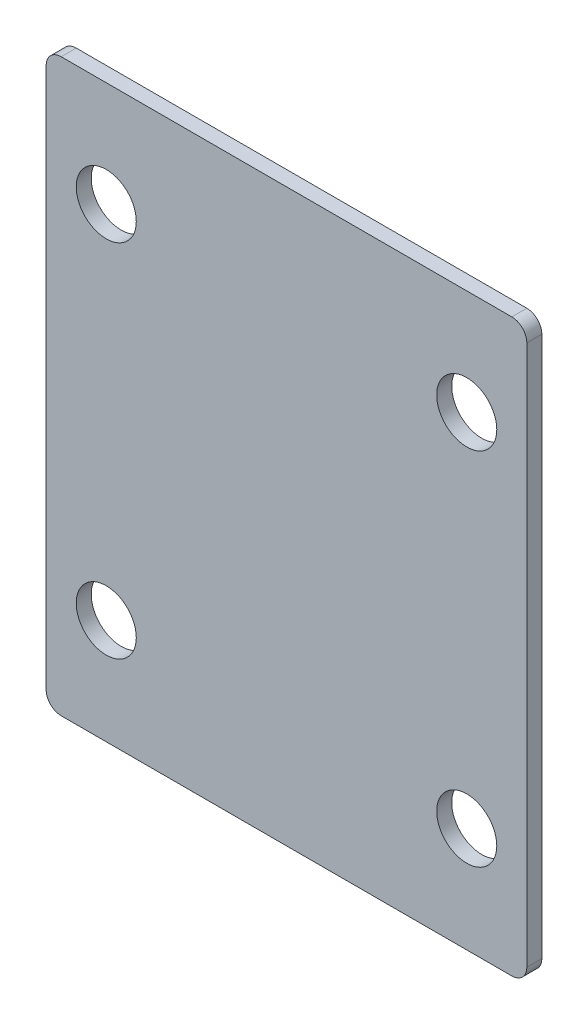
SolidWorks part; units mm, degrees
ref_plane "Front Plane" through (0, 0, 0) normal (0, 0, 1) x (1, 0, 0)
ref_plane "Top Plane" through (0, 0, 0) normal (0, 1, 0) x (1, 0, 0)
ref_plane "Right Plane" through (0, 0, 0) normal (1, 0, 0) x (0, 0, -1)
sketch "Sketch2" plane through (0, 0, 0) normal (0, 0, 1) x (1, 0, 0)
  line L1 (7.5, 9.5) -> (-7.5, 9.5)
  line L2 (8, 9) -> (8, -9)
  line L3 (7.5, -9.5) -> (-7.5, -9.5)
  line L4 (-8, 9) -> (-8, -9)
  line L5 (8, 9.5) -> (-8, -9.5) construction
  line L6 (8, -9.5) -> (-8, 9.5) construction
  line L7 (-8, 9.5) -> (-6, 9.5)
  line L8 (-8, 9.5) -> (-8, 6)
  circle A0 centre (-6, 6) radius 1
  arc A1 (7.5, 9.5) -> (8, 9) centre (7.5, 9) cw
  arc A2 (8, -9) -> (7.5, -9.5) centre (7.5, -9) cw
  arc A3 (-7.5, -9.5) -> (-8, -9) centre (-7.5, -9) cw
  arc A4 (-7.5, 9.5) -> (-8, 9) centre (-7.5, 9) ccw
  circle A5 centre (6, 6) radius 1
  circle A6 centre (6, -6) radius 1
  circle A7 centre (-6, -6) radius 1
  point P0 (0, 0)
  dimension "D5" = 0.5
  dimension "D1" = 16
  dimension "D2" = 19
  dimension "D3" = 2
  dimension "D4" = 3.5
  dimension "D6" = 2
extrude "Boss-Extrude1" add sketch "Sketch2" along normal blind 0.5 contours L1 A4 L4 A3 L3 A2 L2 A1 A7 A6 A5 A0
